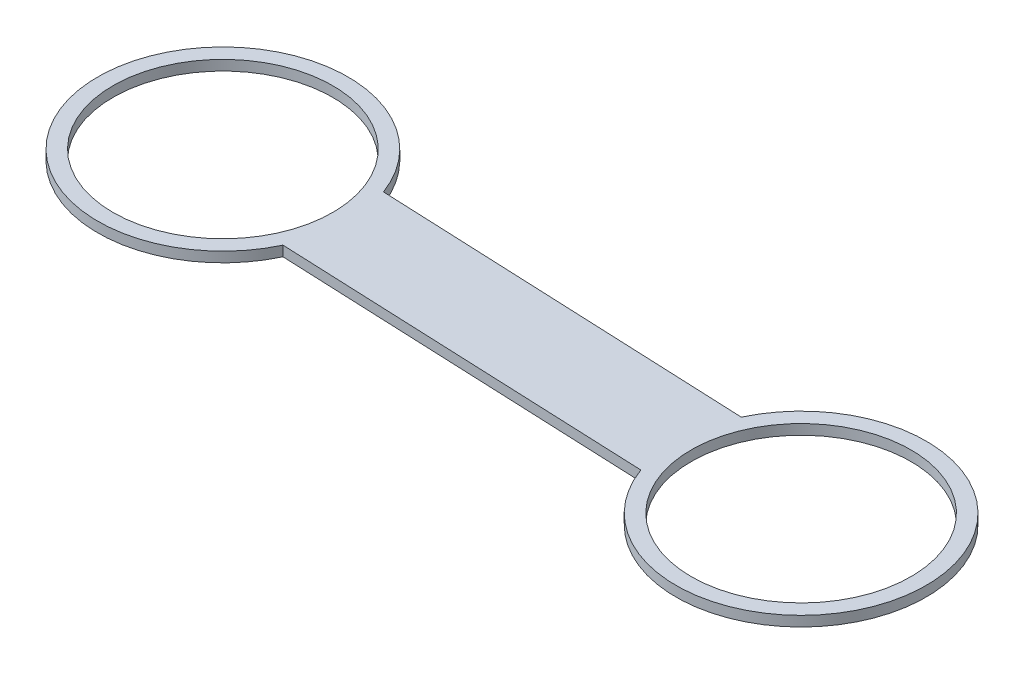
SolidWorks part; units mm, degrees
ref_plane "Front Plane" through (0, 0, 0) normal (0, 0, 1) x (1, 0, 0)
ref_plane "Top Plane" through (0, 0, 0) normal (0, 1, 0) x (1, 0, 0)
ref_plane "Right Plane" through (0, 0, 0) normal (1, 0, 0) x (0, 0, -1)
sketch "Sketch1" plane through (0, 0, 0) normal (0, 1, 0) x (1, 0, 0)
  line L1 (34.7245, 12.7755) -> (145.341, 8)
  line L2 (33.4954, -15.7181) -> (144.0331, -20.4012)
  circle A0 centre (0, 0) radius 32.5
  arc A1 (34.7245, 12.7755) -> (33.4954, -15.7181) centre (0, 0) ccw
  circle A2 centre (178.811, -7.7721) radius 32.5
  arc A3 (144.0331, -20.4012) -> (145.341, 8) centre (178.811, -7.7721) ccw
  point P8 (0, 0)
  point P10 (0, 0)
extrude "Boss-Extrude1" add sketch "Sketch1" along normal blind 3
